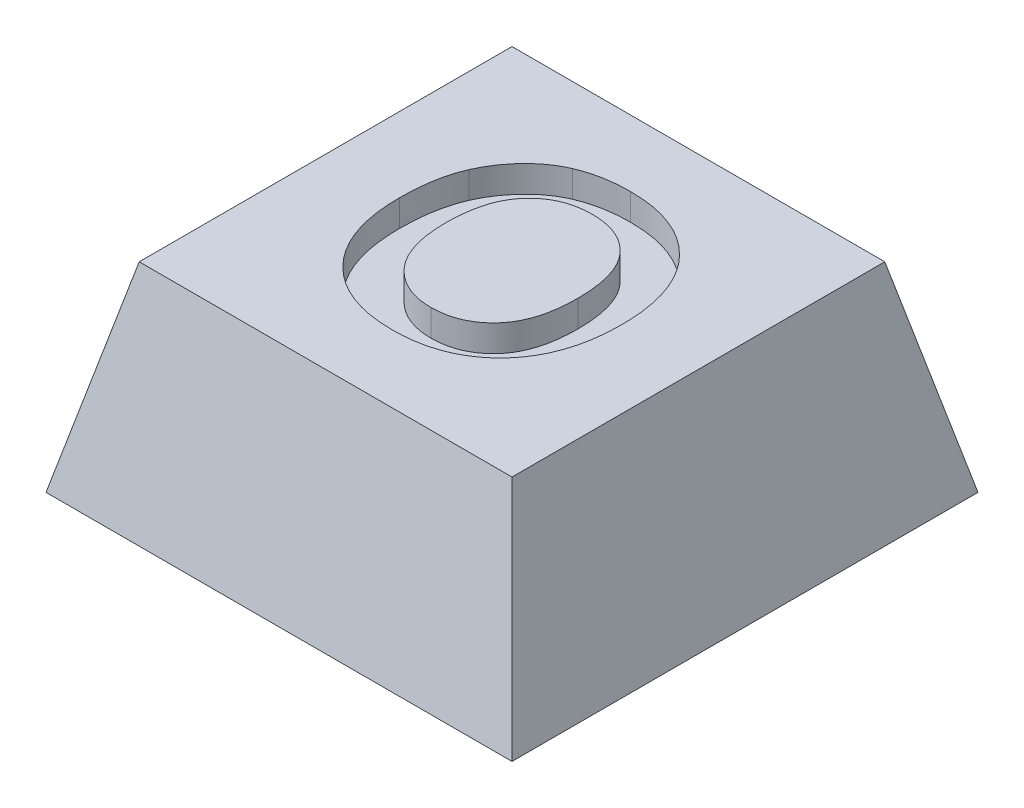
SolidWorks part; units mm, degrees
ref_plane "Front Plane" through (0, 0, 0) normal (0, 0, 1) x (1, 0, 0)
ref_plane "Top Plane" through (0, 0, 0) normal (0, 1, 0) x (1, 0, 0)
ref_plane "Right Plane" through (0, 0, 0) normal (1, 0, 0) x (0, 0, -1)
sketch "Sketch1" plane through (0, 0, 0) normal (0, 1, 0) x (1, 0, 0)
  line L1 (0, 0) -> (7, 0)
  line L2 (0, 0) -> (0, 7)
  line L3 (0, 7) -> (7, 7)
  line L4 (7, 0) -> (7, 7)
  dimension "D1" = 7
  dimension "D2" = 7
extrude "Boss-Extrude1" add sketch "Sketch1" along normal blind 3
sketch "Sketch2" plane through (0, 0, 0) normal (0, 0, 1) x (1, 0, 0)
  line L0 (0, 0) -> (0.7, 3)
  line L1 (0, 3) -> (7, 3) construction
  line L2 (0.7, 3) -> (0, 3)
  line L3 (0, 3) -> (0, 0)
  line L4 (7, 0) -> (6.3, 3)
  line L5 (6.3, 3) -> (7, 3)
  line L6 (7, 3) -> (7, 0)
  dimension "D1" = 0.7
  dimension "D2" = 0.7
extrude "Cut-Extrude1" cut sketch "Sketch2" against normal blind 7
sketch "Sketch3" plane through (0, 0, 0) normal (1, 0, 0) x (0, 0, -1)
  line L0 (0, 0) -> (0.7, 3)
  line L1 (7, 3) -> (0, 3) construction
  line L2 (0.7, 3) -> (0, 3)
  line L3 (0, 3) -> (0, 0)
  line L4 (7, 3) -> (6.3, 3)
  line L5 (6.3, 3) -> (7, 0)
  line L6 (7, 3) -> (7, 0)
  dimension "D1" = 0.7
  dimension "D2" = 0.7
extrude "Cut-Extrude2" cut sketch "Sketch3" along normal blind 11
sketch "Sketch4" plane through (0, 0, 0) normal (0, -1, 0) x (1, 0, 0)
  line L0 (3.5, 0) -> (3.5, -7) construction
  line L1 (0, 0) -> (7, 0) construction
  line L2 (7, -7) -> (0, -7) construction
  line L3 (0, -3.5) -> (7, -3.5) construction
  line L4 (0, -7) -> (0, 0) construction
  line L5 (7, 0) -> (7, -7) construction
  circle A0 centre (3.5, -3.5) radius 1.8
  dimension "D1" = 3.6
extrude "Cut-Extrude3" cut sketch "Sketch4" against normal blind 0.8
sketch "Sketch5" plane through (0, 3, 0) normal (0, 1, 0) x (1, 0, 0)
  text T0 "O" font "Arial" height 3.5
extrude "Cut-Extrude4" cut sketch "Sketch5" against normal blind 0.4
